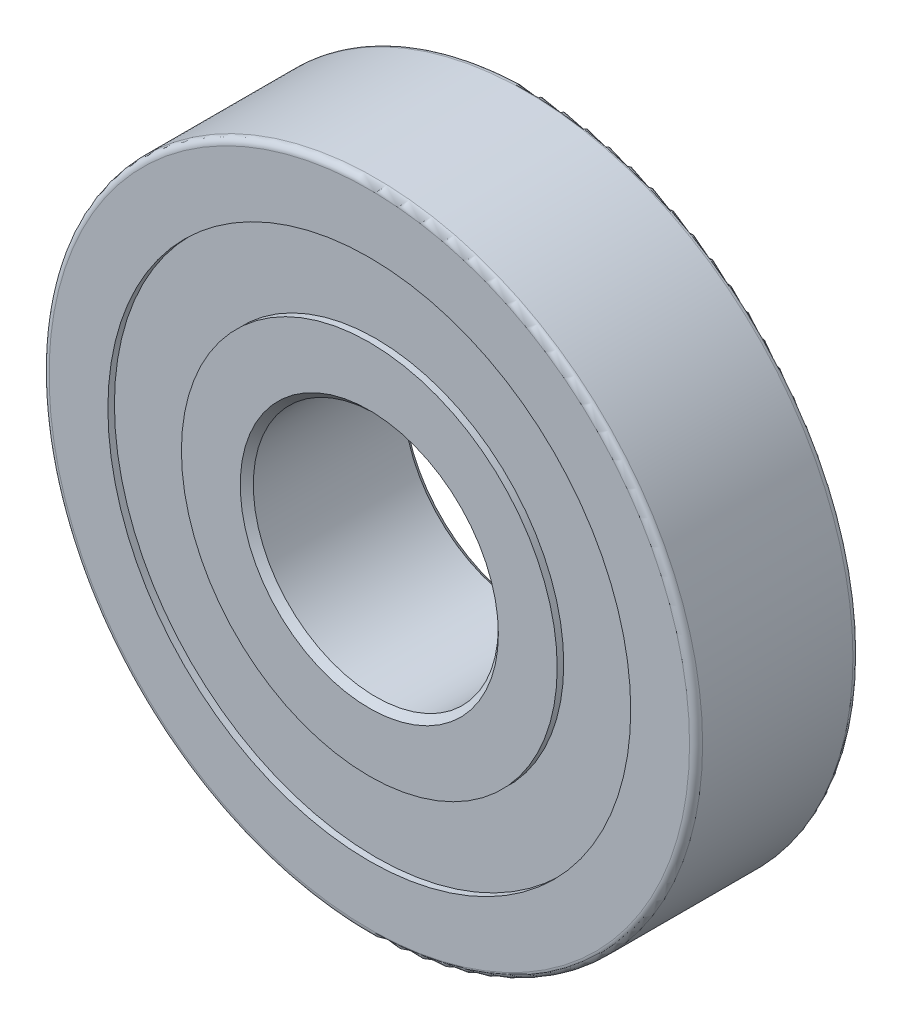
SolidWorks part; units mm, degrees
ref_plane "Front" through (0, 0, 0) normal (0, 0, 1) x (1, 0, 0)
ref_plane "Top" through (0, 0, 0) normal (0, 1, 0) x (1, 0, 0)
ref_plane "Right" through (0, 0, 0) normal (1, 0, 0) x (0, 0, -1)
sketch "Sketch1" plane through (0, 0, 0) normal (0, 0, 1) x (1, 0, 0)
  circle A0 centre (0, 0) radius 6.35
  circle A1 centre (0, 0) radius 2.3812
  circle A2 centre (0, 0) radius 5.08
  circle A3 centre (0, 0) radius 3.6513
  dimension "D1" = 12.7
  dimension "D2" = 4.7625
  dimension "D3" = 1.27
  dimension "D4" = 1.27
extrude "Boss-Extrude1" add sketch "Sketch1" along normal mid plane 3.175 contours A0 A2 | A3 A1
sketch "Sketch2" plane through (0, 0, 0) normal (0, 0, 1) x (1, 0, 0)
  circle A0 centre (0, 0) radius 6.35
  circle A1 centre (0, 0) radius 5.08
  circle A2 centre (0, 0) radius 5.08
  circle A3 centre (0, 0) radius 6.35
  circle A4 centre (0, 0) radius 3.6513 construction
  circle A5 centre (0, 0) radius 3.6513
extrude "Boss-Extrude2" add sketch "Sketch2" along normal mid plane 2.921 contours A2 A5
fillet "Fillet1" radius 0.127 2 edges at (6.35, 0, -1.5875) (6.35, 0, 1.5875)
chamfer "Chamfer1" distance 0.127 angle 45 2 edges at (2.3812, 0, -1.5875) (2.3812, 0, 1.5875)
